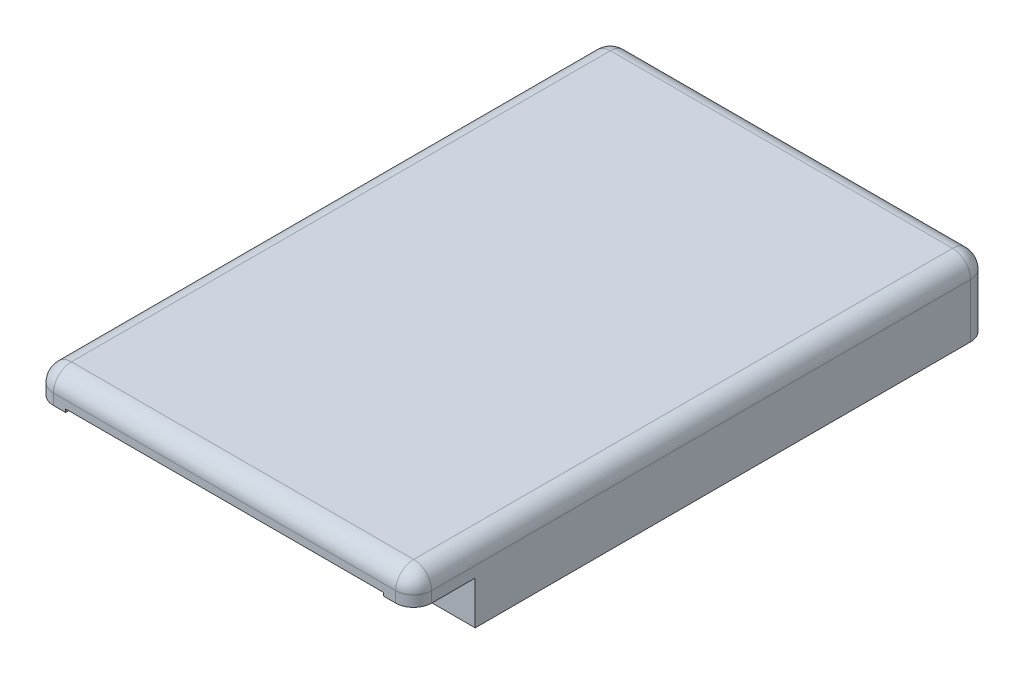
SolidWorks part; units mm, degrees
ref_plane "Front Plane" through (0, 0, 0) normal (0, 0, 1) x (1, 0, 0)
ref_plane "Top Plane" through (0, 0, 0) normal (0, 1, 0) x (1, 0, 0)
ref_plane "Right Plane" through (0, 0, 0) normal (1, 0, 0) x (0, 0, -1)
sketch "Sketch1" plane through (0, 0, 0) normal (0, 0, 1) x (1, 0, 0)
  line L0 (0, 0) -> (26.4, 0) construction
  line L1 (-4.45, 5.15) -> (30.85, 5.15)
  line L4 (0, 0) -> (-7.8, 0)
  line L5 (-7.8, 0) -> (-7.8, 8)
  line L6 (-7.8, 8) -> (34.2, 8)
  line L7 (34.2, 8) -> (34.2, 0)
  line L8 (34.2, 0) -> (26.4, 0)
  line L9 (-4.45, 5.15) -> (-4.45, 2.35)
  line L10 (-4.45, 2.35) -> (0, 2.35)
  line L11 (0, 2.35) -> (0, 0)
  line L12 (30.85, 5.15) -> (30.85, 2.35)
  line L13 (30.85, 2.35) -> (26.4, 2.35)
  line L14 (26.4, 2.35) -> (26.4, 0)
  point P5 (13.2, 5.15)
  point P6 (13.2, 0)
  point P7 (13.2, 8)
  dimension "D1" = 26.4
  dimension "D2" = 35.3
  dimension "D3" = 5.15
  dimension "D4" = 42
  dimension "D5" = 8
  dimension "D6" = 2.8
  dimension "D7" = 2.8
extrude "Boss-Extrude1" add sketch "Sketch1" along normal blind 63.83
sketch "Sketch2" plane through (0, 0, 63.83) normal (0, 0, 1) x (1, 0, 0)
  line L0 (-7.8, 4.8) -> (34.2, 4.8)
  line L1 (-7.8, 8) -> (-7.8, 0) construction
  line L2 (34.2, 0) -> (34.2, 8) construction
  line L3 (34.2, 4.8) -> (34.2, 0)
  line L4 (34.2, 0) -> (-7.8, 0)
  line L5 (-7.8, 0) -> (-7.8, 4.8)
extrude "Cut-Extrude1" cut sketch "Sketch2" against normal blind 6.83
fillet "Fillet1" radius 2 8 edges at (34.2, 8, 31.915) (13.2, 8, 63.83) (-7.8, 8, 31.915) (13.2, 8, 0) (-7.8, 6.4, 63.83) (34.2, 6.4, 63.83) (-7.8, 4, 0) (34.2, 4, 0)
